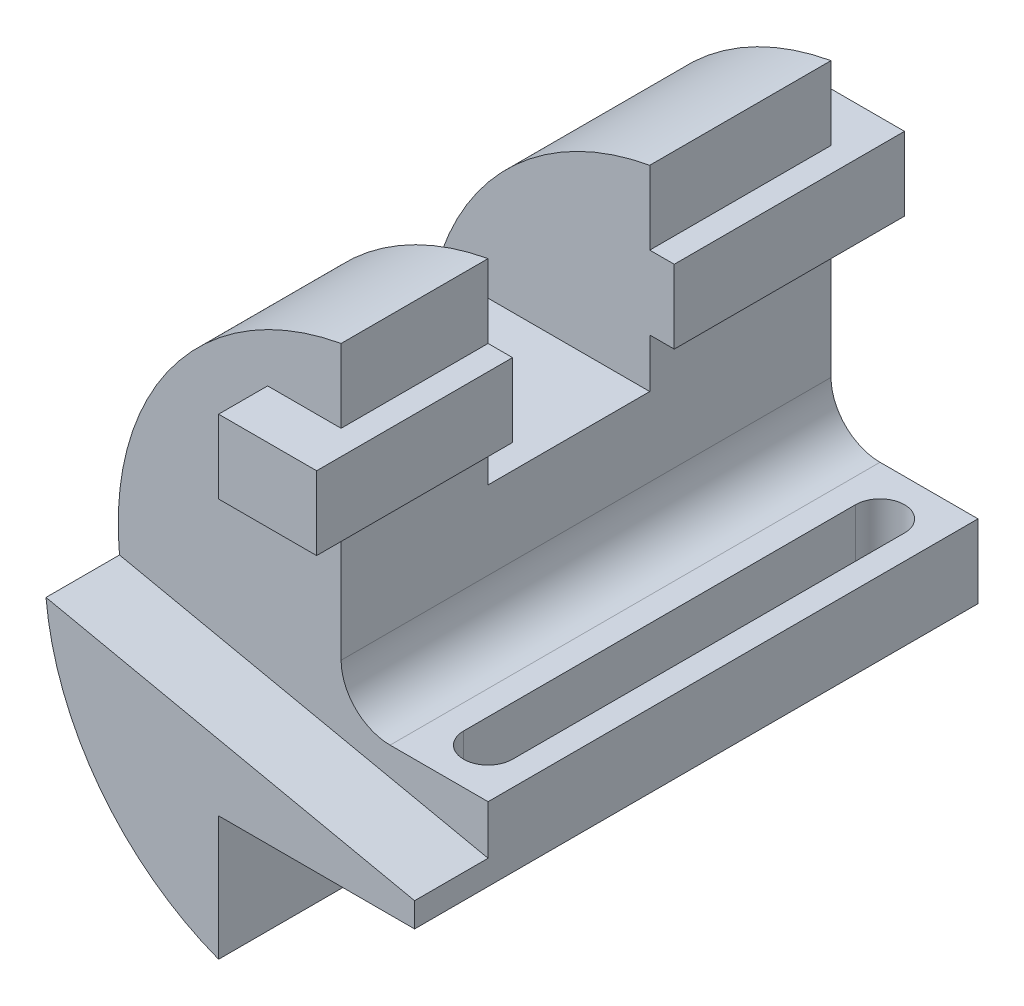
SolidWorks part; units mm, degrees
material "1060 Alloy"
ref_plane "Front Plane" through (0, 0, 0) normal (0, 0, 1) x (1, 0, 0)
ref_plane "Top Plane" through (0, 0, 0) normal (0, 1, 0) x (1, 0, 0)
ref_plane "Right Plane" through (0, 0, 0) normal (1, 0, 0) x (0, 0, -1)
sketch "Sketch1" plane through (0, 0, 0) normal (0, 0, 1) x (1, 0, 0)
  line L0 (0, 55) -> (0, -55) construction
  line L1 (-55.5, 0) -> (55, 0) construction
  line L2 (-10, 54.5917) -> (-10, -1.4083)
  line L3 (0, -11.4083) -> (20, -11.4083)
  line L4 (20, -11.4083) -> (20, -26.4083)
  line L5 (20, -26.4083) -> (-20, -26.4083)
  line L6 (-20, -26.4083) -> (-20, -51.7711)
  arc A1 (-10, 54.5917) -> (-20, -51.7711) centre (0, 0) ccw
  arc A3 (-10, -1.4083) -> (0, -11.4083) centre (0, -1.4083) ccw
  dimension "D1" = 111
  dimension "D2" = 66
  dimension "D4" = 10
  dimension "D5" = 15
  dimension "D3" = 10
  dimension "D6" = 40
  dimension "D7" = 20
extrude "Boss-Extrude1" add sketch "Sketch1" along normal blind 100
sketch "Sketch4" plane through (-10, 0, 0) normal (1, 0, 0) x (0, 0, -1)
  line L0 (-70, 54.5917) -> (-70, 14.5917)
  line L1 (-100, 54.5917) -> (0, 54.5917) construction
  line L2 (-70, 14.5917) -> (-37, 14.5917)
  line L3 (-37, 14.5917) -> (-37, 54.5917)
  line L4 (-37, 54.5917) -> (-70, 54.5917)
  dimension "D1" = 30
  dimension "D2" = 33
  dimension "D3" = 40
extrude "Cut-Extrude1" cut sketch "Sketch4" against normal up to next
sketch "Sketch5" plane through (-10, 0, 0) normal (1, 0, 0) x (0, 0, -1)
  line L0 (-70, 39.5917) -> (-110, 39.5917)
  line L1 (-70, 54.5917) -> (-70, 14.5917) construction
  line L2 (-110, 39.5917) -> (-110, 24.5917)
  line L3 (-110, 24.5917) -> (-70, 24.5917)
  line L4 (-70, 24.5917) -> (-70, 39.5917)
  dimension "D1" = 15
  dimension "D2" = 15
  dimension "D3" = 40
extrude "Boss-Extrude2" add sketch "Sketch5" along normal mid plane 30
sketch "Sketch6" plane through (5, 0, 0) normal (1, 0, 0) x (0, 0, -1)
  line L0 (-110, 24.5917) -> (-110, 39.5917)
  line L1 (-110, 39.5917) -> (-70, 39.5917)
  line L2 (-70, 39.5917) -> (-70, 24.5917)
  line L3 (-70, 24.5917) -> (-110, 24.5917)
extrude "Cut-Extrude2" cut sketch "Sketch6" against normal blind 10
sketch "Sketch7" plane through (-10, 0, 0) normal (1, 0, 0) x (0, 0, -1)
  line L0 (-37, 39.5917) -> (10, 39.5917)
  line L1 (-37, 14.5917) -> (-37, 54.5917) construction
  line L2 (-37, 24.5917) -> (10, 24.5917)
  line L3 (10, 24.5917) -> (10, 39.5917)
  line L4 (-37, 24.5917) -> (-37, 39.5917)
  line L5 (0, -1.4083) -> (0, 54.5917) construction
  dimension "D1" = 15
  dimension "D2" = 15
  dimension "D3" = 10
extrude "Boss-Extrude3" add sketch "Sketch7" along normal mid plane 10
sketch "Sketch8" plane through (-5, 0, 0) normal (1, 0, 0) x (0, 0, -1)
  line L0 (-37, 39.5917) -> (-37, 24.5917)
  line L1 (-37, 24.5917) -> (10, 24.5917)
  line L2 (10, 24.5917) -> (10, 39.5917)
  line L3 (10, 39.5917) -> (-37, 39.5917)
extrude "Boss-Extrude4" add sketch "Sketch8" against normal blind 20
sketch "Sketch9" plane through (0, -11.4083, 0) normal (0, 1, 0) x (1, 0, 0)
  line L0 (10, -10) -> (10, -90) construction
  line L1 (15, -10) -> (15, -90)
  line L2 (5, -10) -> (5, -90)
  line L3 (20, -50) -> (0, -50) construction
  line L4 (20, -100) -> (20, 0) construction
  line L5 (0, -100) -> (0, 0) construction
  arc A0 (15, -10) -> (5, -10) centre (10, -10) ccw
  arc A1 (5, -90) -> (15, -90) centre (10, -90) ccw
  point P2 (10, -50)
  dimension "D2" = 5
  dimension "D1" = 80
extrude "Cut-Extrude3" cut sketch "Sketch9" against normal through all
sketch "Sketch10" plane through (0, 0, 100) normal (0, 0, 1) x (1, 0, 0)
  line L0 (20, -26.4083) -> (20, -21.4083)
  line L1 (20, -26.4083) -> (20, -11.4083) construction
  line L2 (20, -21.4083) -> (-55.235, -5.4166)
  line L3 (20, -26.4083) -> (-20, -26.4083)
  line L4 (-20, -26.4083) -> (-20, -51.7711)
  arc A0 (-10, 54.5917) -> (-20, -51.7711) centre (0, 0) ccw construction
  arc A1 (-55.235, -5.4166) -> (-20, -51.7711) centre (-0.4684, -0.356) ccw
  dimension "D1" = 5
  dimension "D3" = 55
  dimension "D2" = 78
extrude "Boss-Extrude5" add sketch "Sketch10" along normal blind 15
equation "\"A\"= 55.50"
equation "\"B\"= 66"
equation "\"C\"= 33"
